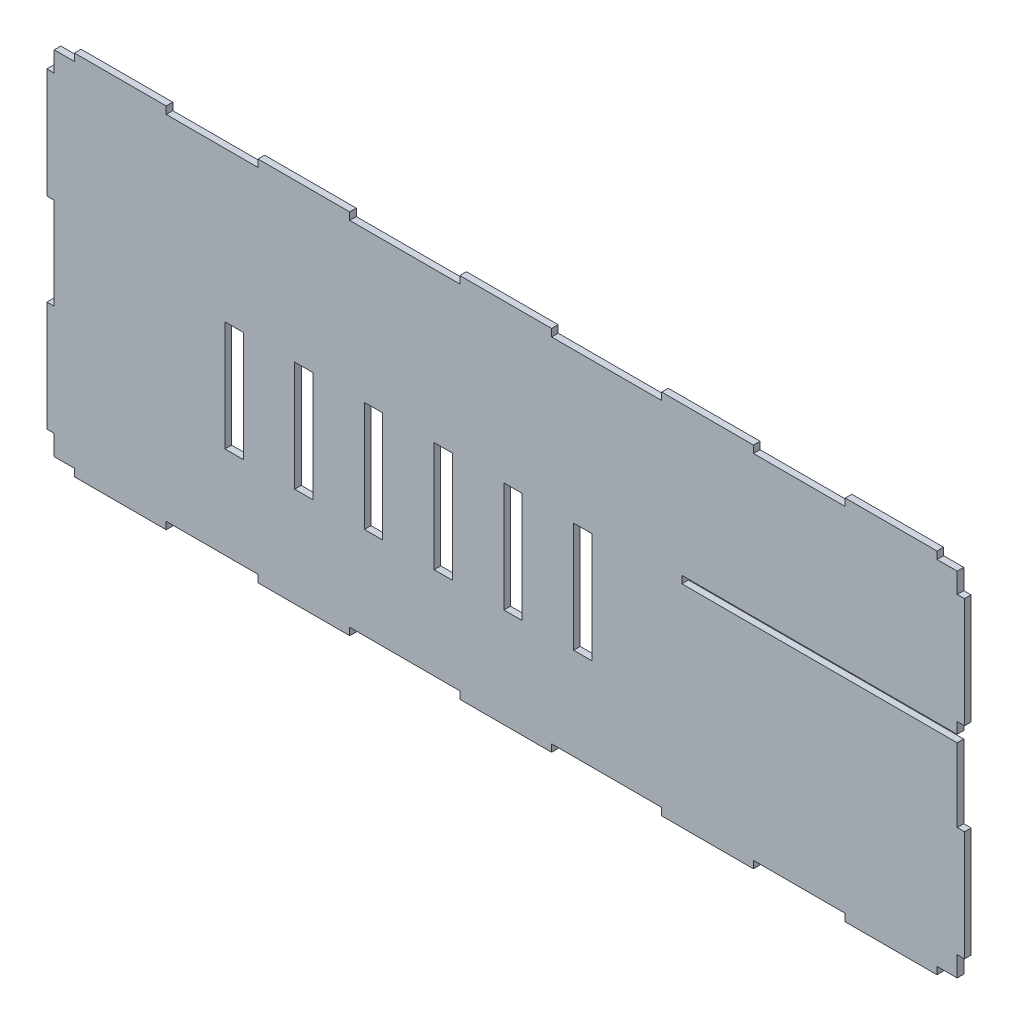
SolidWorks part; units mm, degrees
material "处理板，复杂型"
ref_plane "前视基准面" through (0, 0, 0) normal (0, 0, 1) x (1, 0, 0)
ref_plane "上视基准面" through (0, 0, 0) normal (0, 1, 0) x (1, 0, 0)
ref_plane "右视基准面" through (0, 0, 0) normal (1, 0, 0) x (0, 0, -1)
sketch "草图1" plane through (0, 0, 0) normal (0, 0, 1) x (1, 0, 0)
  line L0 (-342.2535, 0) -> (646.4789, 0) construction
  line L1 (-250, 100) -> (250, 100)
  line L2 (-250, 100) -> (-250, -100)
  line L3 (-250, -100) -> (250, -100)
  line L4 (250, 100) -> (250, -100)
  line L5 (0, 347.1831) -> (0, -385.2113) construction
  dimension "D1" = 200
  dimension "D2" = 500
  dimension "D3" = 250
  dimension "D4" = 100
extrude "凸台-拉伸1" add sketch "草图1" along normal blind 3.6
sketch "草图3" plane through (0, 0, 3.6) normal (0, 0, 1) x (1, 0, 0)
  line L0 (-246, 192.9658) -> (-246, -192.96) construction
  line L1 (246, 192.9658) -> (246, -192.96) construction
  line L2 (250, -100) -> (250, 100) construction
  line L3 (-250, 100) -> (-250, -100) construction
  line L4 (-300.7416, 0) -> (304.897, 0) construction
  line L5 (0, 188.291) -> (0, -192.96) construction
  line L7 (-246, 25) -> (-250, 25)
  line L8 (-246, 25) -> (-246, -25)
  line L9 (-246, -25) -> (-250, -25)
  line L10 (-250, 25) -> (-250, -25)
  line L11 (-246, 135) -> (-250, 135)
  line L12 (-246, 135) -> (-246, 85)
  line L13 (-246, 85) -> (-250, 85)
  line L14 (-250, 135) -> (-250, 85)
  line L15 (-246, -85) -> (-250, -85)
  line L16 (-246, -85) -> (-246, -135)
  line L17 (-246, -135) -> (-250, -135)
  line L18 (-250, -85) -> (-250, -135)
  line L19 (246, 135) -> (250, 135)
  line L20 (246, 135) -> (246, 85)
  line L21 (246, 85) -> (250, 85)
  line L22 (250, 135) -> (250, 85)
  line L23 (246, 25) -> (250, 25)
  line L24 (246, 25) -> (246, -25)
  line L25 (246, -25) -> (250, -25)
  line L26 (250, 25) -> (250, -25)
  line L27 (246, -85) -> (250, -85)
  line L28 (246, -85) -> (246, -135)
  line L29 (246, -135) -> (250, -135)
  line L30 (250, -85) -> (250, -135)
  dimension "D1" = 4
  dimension "D2" = 4
  dimension "D3" = 50
  dimension "D4" = 25
  dimension "D5" = 50
  dimension "D6" = 60
  dimension "D7" = 60
  dimension "D8" = 50
  dimension "D9" = 50
  dimension "D10" = 50
  dimension "D11" = 50
  dimension "D12" = 25
  dimension "D13" = 60
  dimension "D14" = 60
extrude "切除-拉伸2" cut sketch "草图3" against normal blind 3.6
sketch "草图4" plane through (0, 0, 3.6) normal (0, 0, 1) x (1, 0, 0)
  line L0 (-291.9116, -96) -> (-235, -96)
  line L1 (-246, -100) -> (246, -100) construction
  line L2 (0, 145.1767) -> (0, -169.5892) construction
  line L3 (-311.1299, 0) -> (273.2126, 0) construction
  line L4 (-185, -96) -> (-135, -96)
  line L6 (-25, -96) -> (-25, -100)
  line L8 (25, -96) -> (25, -100)
  line L10 (-135, -96) -> (-135, -100)
  line L12 (-85, -96) -> (-85, -100)
  line L14 (-235, -96) -> (-235, -100)
  line L16 (-185, -96) -> (-185, -100)
  line L18 (85, -96) -> (85, -100)
  line L20 (135, -96) -> (135, -100)
  line L22 (185, -96) -> (185, -100)
  line L24 (235, -96) -> (235, -100)
  line L25 (-85, -96) -> (-25, -96)
  line L26 (25, -96) -> (85, -96)
  line L27 (135, -96) -> (185, -96)
  line L28 (235, -96) -> (292.9617, -96)
  line L29 (-291.9116, -96) -> (-291.9116, -100)
  line L30 (-291.9116, -100) -> (-235, -100)
  line L31 (-185, -100) -> (-135, -100)
  line L32 (-85, -100) -> (-25, -100)
  line L33 (25, -100) -> (85, -100)
  line L34 (135, -100) -> (185, -100)
  line L35 (235, -100) -> (292.9617, -100)
  line L36 (292.9617, -100) -> (292.9617, -96)
  line L37 (235, 100) -> (292.9617, 100)
  line L38 (235, 96) -> (235, 100)
  line L39 (235, 96) -> (292.9617, 96)
  line L40 (292.9617, 100) -> (292.9617, 96)
  line L41 (135, 96) -> (135, 100)
  line L42 (135, 96) -> (185, 96)
  line L43 (185, 96) -> (185, 100)
  line L44 (135, 100) -> (185, 100)
  line L45 (25, 96) -> (25, 100)
  line L46 (25, 96) -> (85, 96)
  line L47 (85, 96) -> (85, 100)
  line L48 (25, 100) -> (85, 100)
  line L49 (-85, 96) -> (-85, 100)
  line L50 (-85, 96) -> (-25, 96)
  line L51 (-25, 96) -> (-25, 100)
  line L52 (-85, 100) -> (-25, 100)
  line L53 (-185, 96) -> (-185, 100)
  line L54 (-185, 96) -> (-135, 96)
  line L55 (-135, 96) -> (-135, 100)
  line L56 (-185, 100) -> (-135, 100)
  line L57 (-291.9116, 96) -> (-291.9116, 100)
  line L58 (-291.9116, 96) -> (-235, 96)
  line L59 (-235, 96) -> (-235, 100)
  line L60 (-291.9116, 100) -> (-235, 100)
  dimension "D1" = 4
  dimension "D2" = 50
  dimension "D3" = 25
  dimension "D4" = 50
  dimension "D5" = 50
  dimension "D6" = 50
  dimension "D7" = 50
  dimension "D8" = 60
  dimension "D9" = 50
  dimension "D10" = 60
  dimension "D11" = 50
extrude "切除-拉伸3" cut sketch "草图4" against normal blind 10
sketch "草图5" plane through (0, 0, 3.6) normal (0, 0, 1) x (1, 0, 0)
  line L1 (-258.4798, -15.8374) -> (279.114, -15.8374) construction
  line L3 (-153, 14.1626) -> (-143, 14.1626)
  line L4 (-153, 14.1626) -> (-153, -45.8374)
  line L5 (-153, -45.8374) -> (-143, -45.8374)
  line L6 (-143, 14.1626) -> (-143, -45.8374)
  line L7 (-115, 14.1626) -> (-105, 14.1626)
  line L8 (-115, 14.1626) -> (-115, -45.8374)
  line L9 (-115, -45.8374) -> (-105, -45.8374)
  line L10 (-105, 14.1626) -> (-105, -45.8374)
  line L11 (-77, 14.1626) -> (-67, 14.1626)
  line L12 (-77, 14.1626) -> (-77, -45.8374)
  line L13 (-77, -45.8374) -> (-67, -45.8374)
  line L14 (-67, 14.1626) -> (-67, -45.8374)
  line L15 (-39, 14.1626) -> (-29, 14.1626)
  line L16 (-39, 14.1626) -> (-39, -45.8374)
  line L17 (-39, -45.8374) -> (-29, -45.8374)
  line L18 (-29, 14.1626) -> (-29, -45.8374)
  line L19 (-1, 14.1626) -> (9, 14.1626)
  line L20 (-1, 14.1626) -> (-1, -45.8374)
  line L21 (-1, -45.8374) -> (9, -45.8374)
  line L22 (9, 14.1626) -> (9, -45.8374)
  line L23 (37, 14.1626) -> (47, 14.1626)
  line L24 (37, 14.1626) -> (37, -45.8374)
  line L25 (37, -45.8374) -> (47, -45.8374)
  line L26 (47, 14.1626) -> (47, -45.8374)
  dimension "D1" = 10
  dimension "D2" = 60
  dimension "D3" = 30
  dimension "D4" = 10
  dimension "D5" = 10
  dimension "D6" = 10
  dimension "D7" = 10
  dimension "D8" = 10
  dimension "D9" = 60
  dimension "D10" = 60
  dimension "D11" = 60
  dimension "D12" = 60
  dimension "D13" = 60
  dimension "D14" = 0
  dimension "D15" = 0
  dimension "D16" = 0
  dimension "D17" = 0
  dimension "D18" = 0
extrude "切除-拉伸4" cut sketch "草图5" against normal through all
sketch "草图6" plane through (0, 0, 3.6) normal (0, 0, 1) x (1, 0, 0)
  line L0 (96, 15) -> (359.4929, 15)
  line L1 (246, 25) -> (246, -25) construction
  line L2 (96, 15) -> (290.8996, 15)
  line L3 (96, 15) -> (96, 19)
  line L4 (96, 19) -> (290.8996, 19)
  line L5 (290.8996, 15) -> (290.8996, 19)
  dimension "D1" = 15
  dimension "D2" = 4
  dimension "D3" = 150
extrude "切除-拉伸5" cut sketch "草图6" against normal through all contours L0 L5 L4 L3
